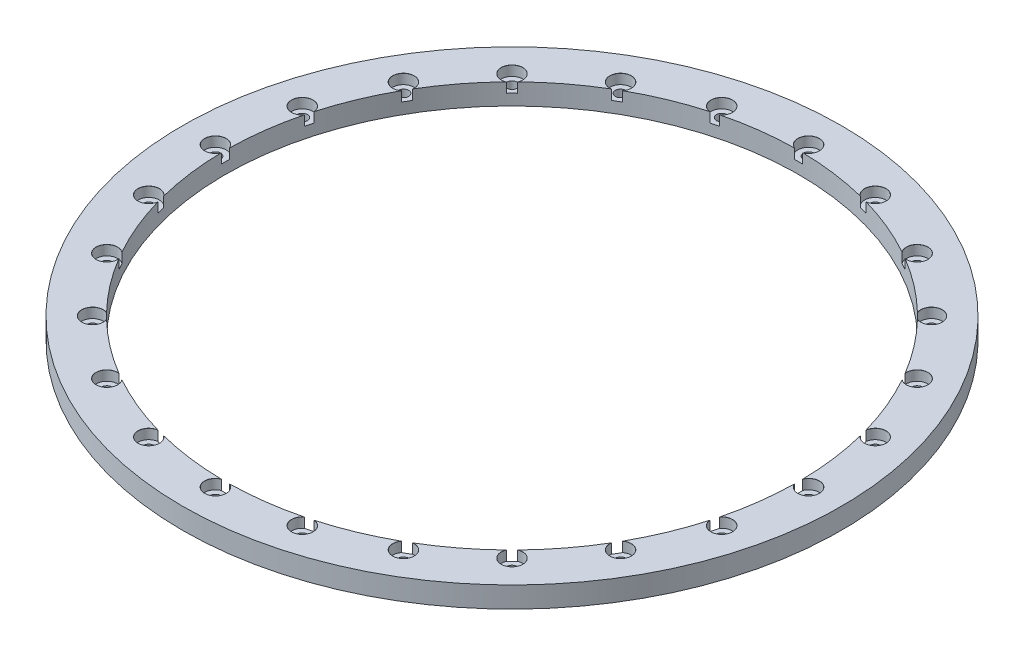
SolidWorks part; units mm, degrees
material "Delrin 2700 NC010, Low Viscosity Acetal Copolymer (SS)"
ref_plane "Front Plane" through (0, 0, 0) normal (0, 0, 1) x (1, 0, 0)
ref_plane "Top Plane" through (0, 0, 0) normal (0, 1, 0) x (1, 0, 0)
ref_plane "Right Plane" through (0, 0, 0) normal (1, 0, 0) x (0, 0, -1)
sketch "Sketch1" plane through (0, 0, 0) normal (0, 1, 0) x (1, 0, 0)
  circle A0 centre (0, 0) radius 100
  circle A1 centre (0, 0) radius 87
  dimension "D1" = 200
  dimension "D2" = 174
extrude "Boss-Extrude1" add sketch "Sketch1" along normal blind 6.35
hole_wizard "CBORE for M3 SHCS1" positions "Sketch2" profile "Sketch3" counterbore size "M3" standard "ANSI Metric" end condition through all
sketch "Sketch2" plane through (0, 6.35, 0) normal (0, 1, 0) x (1, 0, 0)
  line L0 (0, 0) -> (90, 0) construction
  point P0 (90, 0)
  point P15 (86.9333, -23.2937)
  point P16 (77.9423, -45)
  point P17 (63.6396, -63.6396)
  point P18 (45, -77.9423)
  point P19 (23.2937, -86.9333)
  point P20 (0, -90)
  point P21 (-23.2937, -86.9333)
  point P22 (-45, -77.9423)
  point P23 (-63.6396, -63.6396)
  point P24 (-77.9423, -45)
  point P25 (-86.9333, -23.2937)
  point P26 (-90, 0)
  point P27 (-86.9333, 23.2937)
  point P28 (-77.9423, 45)
  point P29 (-63.6396, 63.6396)
  point P30 (-45, 77.9423)
  point P31 (-23.2937, 86.9333)
  point P32 (0, 90)
  point P33 (23.2937, 86.9333)
  point P34 (45, 77.9423)
  point P35 (63.6396, 63.6396)
  point P36 (77.9423, 45)
  point P37 (86.9333, 23.2937)
  point P39 (95, 0)
  point P40 (0, 0)
  point P41 (0, 0)
  point P43 (0, 0)
  point P45 (7.5279, 4.0982)
  point P46 (116.3538, 6.2463)
  point P47 (0, 0)
  point P49 (0, 0)
  point P50 (4.472, 6.2931)
  point P51 (0, 0)
  point P52 (0, 0)
  point P54 (90, 0)
  point P55 (90, 0)
  dimension "D1" = 90
  dimension "D2" = 24
sketch "Sketch3" plane through (90, 6.35, 0) normal (1, 0, 0) x (0, 0, 1)
  line L0 (0, 0) -> (0, 6.35)
  line L1 (0, 6.35) -> (1.6, 6.35)
  line L3 (1.6, 6.35) -> (1.6, 3)
  line L4 (3.25, 3) -> (1.6, 3)
  line L5 (3.25, 3) -> (3.25, 0.025)
  line L6 (3.25, 0.025) -> (3.275, 0)
  line L7 (3.275, 0) -> (0, 0)
  line L8 (-3.25, 0.025) -> (-3.275, 0) construction
  line L11 (0, -6.35) -> (0, 107.95) construction
  dimension "Thru Hole Dia." = 3.2
  dimension "Thru Hole Depth" = 6.35
  dimension "C'Bore Dia." = 6.5
  dimension "C'Bore Depth" = 3
  dimension "Near C'Sink Dia." = 6.55
  dimension "Near C'Sink Angle" = 90
